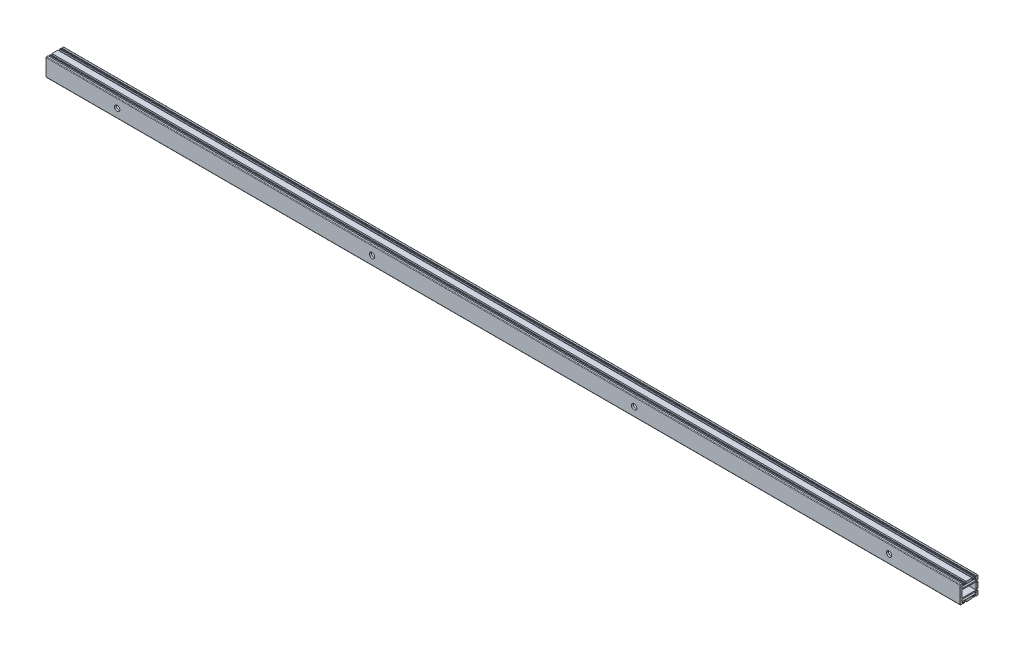
SolidWorks part; units mm, degrees
ref_plane "前视基准面" through (0, 0, 0) normal (0, 0, 1) x (1, 0, 0)
ref_plane "上视基准面" through (0, 0, 0) normal (0, 1, 0) x (1, 0, 0)
ref_plane "右视基准面" through (0, 0, 0) normal (1, 0, 0) x (0, 0, -1)
sketch "草图1" plane through (0, 0, 0) normal (1, 0, 0) x (0, 0, -1)
  line L0 (-15, 15) -> (15, -15) construction
  line L1 (-14, 15) -> (-11.5, 15)
  line L2 (-15, 14) -> (-15, -14)
  line L3 (-14, -15) -> (-11.5, -15)
  line L4 (15, 14) -> (15, 8)
  line L5 (15, 15) -> (-15, -15) construction
  line L6 (-11.5, 15) -> (-11.5, 13.5)
  line L7 (-11.5, 13.5) -> (-11.4, 13.5)
  line L8 (-11, 13.1) -> (-11, 12)
  line L9 (-11, 12) -> (-9.5, 12)
  line L10 (-9.5, 12) -> (-9.5, 15)
  line L11 (-9.5, 15) -> (-8, 15)
  line L12 (-8, 15) -> (-8, 12.5)
  line L13 (-8, 12.5) -> (-5, 12.5)
  line L14 (-5, 12.5) -> (-5, 15)
  line L15 (-5, 15) -> (5, 15)
  line L16 (0, 21.5201) -> (0, -18.309) construction
  line L17 (0, 55) -> (0, -55) construction
  line L18 (5, 12.5) -> (5, 15)
  line L19 (8, 12.5) -> (5, 12.5)
  line L20 (8, 15) -> (8, 12.5)
  line L21 (9.5, 15) -> (8, 15)
  line L22 (9.5, 12) -> (9.5, 15)
  line L23 (11, 12) -> (9.5, 12)
  line L24 (11, 13.1) -> (11, 12)
  line L25 (11.5, 13.5) -> (11.4, 13.5)
  line L26 (11.5, 15) -> (11.5, 13.5)
  line L27 (8, 15) -> (9.5, 15)
  line L28 (11.5, 15) -> (14, 15)
  line L29 (-19.8303, 0) -> (22.13, 0) construction
  line L30 (55, 0) -> (-55, 0) construction
  line L31 (8, -15) -> (9.5, -15)
  line L32 (11.5, -15) -> (11.5, -13.5)
  line L33 (11.5, -13.5) -> (11.4, -13.5)
  line L34 (11, -13.1) -> (11, -12)
  line L35 (11, -12) -> (9.5, -12)
  line L36 (9.5, -12) -> (9.5, -15)
  line L37 (9.5, -15) -> (8, -15)
  line L38 (8, -15) -> (8, -12.5)
  line L39 (8, -12.5) -> (5, -12.5)
  line L40 (5, -12.5) -> (5, -15)
  line L41 (-5, -15) -> (5, -15)
  line L42 (-5, -12.5) -> (-5, -15)
  line L43 (-8, -12.5) -> (-5, -12.5)
  line L44 (-8, -15) -> (-8, -12.5)
  line L45 (-9.5, -15) -> (-8, -15)
  line L46 (-9.5, -12) -> (-9.5, -15)
  line L47 (-11, -12) -> (-9.5, -12)
  line L48 (-11, -13.1) -> (-11, -12)
  line L49 (-11.5, -13.5) -> (-11.4, -13.5)
  line L50 (-11.5, -15) -> (-11.5, -13.5)
  line L51 (-9.5, -15) -> (-8, -15)
  line L52 (-5, -15) -> (5, -15)
  line L53 (8, -15) -> (9.5, -15)
  line L54 (11.5, -15) -> (14, -15)
  line L55 (15, 8) -> (12.5, 8)
  line L56 (12.5, 8) -> (12.5, 5)
  line L57 (12.5, 5) -> (15, 5)
  line L58 (12.5, -5) -> (15, -5)
  line L59 (12.5, -8) -> (12.5, -5)
  line L60 (15, -8) -> (12.5, -8)
  line L61 (15, 5) -> (15, -5)
  line L62 (15, -8) -> (15, -14)
  line L63 (12, -10.5) -> (12, -8.5)
  line L64 (-11.5, 11) -> (11.5, 11)
  line L65 (-12, 10.5) -> (-12, 8.5)
  line L66 (-11.5, 8) -> (11.5, 8)
  line L67 (12, 10.5) -> (12, 8.5)
  line L68 (-11.5, -8) -> (11.5, -8)
  line L69 (-12, -10.5) -> (-12, -8.5)
  line L70 (-11.5, -11) -> (11.5, -11)
  line L72 (-11.75, 6) -> (11.75, 6)
  line L73 (-11.75, 6) -> (-11.75, -6)
  line L74 (-11.75, -6) -> (11.75, -6)
  line L75 (11.75, 6) -> (11.75, -6)
  arc A0 (12, 8.5) -> (11.5, 8) centre (11.5, 8.5) cw
  arc A1 (11.5, 11) -> (12, 10.5) centre (11.5, 10.5) cw
  arc A2 (-11.5, 11) -> (-12, 10.5) centre (-11.5, 10.5) ccw
  arc A3 (-11.5, 8) -> (-12, 8.5) centre (-11.5, 8.5) cw
  arc A4 (-11, -13.1) -> (-11.4, -13.5) centre (-11.4, -13.1) cw
  arc A5 (11.4, -13.5) -> (11, -13.1) centre (11.4, -13.1) cw
  arc A6 (11.4, 13.5) -> (11, 13.1) centre (11.4, 13.1) ccw
  arc A7 (-11, 13.1) -> (-11.4, 13.5) centre (-11.4, 13.1) ccw
  arc A8 (-11.5, -8) -> (-12, -8.5) centre (-11.5, -8.5) ccw
  arc A9 (-11.5, -11) -> (-12, -10.5) centre (-11.5, -10.5) cw
  arc A10 (11.5, -11) -> (12, -10.5) centre (11.5, -10.5) ccw
  arc A11 (12, -8.5) -> (11.5, -8) centre (11.5, -8.5) ccw
  arc A12 (14, 15) -> (15, 14) centre (14, 14) cw
  arc A13 (14, -15) -> (15, -14) centre (14, -14) ccw
  arc A14 (-15, -14) -> (-14, -15) centre (-14, -14) ccw
  arc A15 (-15, 14) -> (-14, 15) centre (-14, 14) cw
  point P69 (12, 11)
  point P72 (-12, 11)
  point P77 (-11, -13.5)
  point P80 (11, -13.5)
  point P83 (11, 13.5)
  point P86 (-11, 13.5)
  point P99 (-12, -11)
  point P100 (12, -11)
  dimension "D17" = 0.5
  dimension "D18" = 0.4
  dimension "D21" = 1
  dimension "D1" = 3.5
  dimension "D2" = 1.5
  dimension "D3" = 0.5
  dimension "D4" = 1.5
  dimension "D5" = 3
  dimension "D6" = 30
  dimension "D7" = 30
  dimension "D8" = 1.5
  dimension "D9" = 2.5
  dimension "D10" = 3
  dimension "D11" = 2.5
  dimension "D12" = 7
  dimension "D13" = 3
  dimension "D14" = 4
  dimension "D15" = 3
  dimension "D16" = 24
  dimension "D19" = 23.5
  dimension "D20" = 12
extrude "凸台-拉伸1" add sketch "草图1" along normal mid plane 1542 contours A15 L2 A14 L3 L50 L49 A4 L48 L47 L46 L45 L44 L43 L42 L41 L40 L39 L38 L31 L36 L35 L34 A5 L33 L32 L54 A13 L62 L60 L59 L58 L61 L57 L56 L55 L4 A12 L28 L26 L25 A6 L24 L23 L22 L21 L20 L19 L18 L15 L14 L13
hole_wizard "M6 螺纹孔1" positions "草图3" profile "草图2" tap size "M6" standard "GB"
sketch "草图3" plane through (0, 0, -15) normal (0, 0, -1) x (-1, 0, 0)
  line L0 (771, 5) -> (771, -5) construction
  line L1 (-771, 15) -> (771, 15) construction
  point P0 (751, 0)
  point P1 (736, 0)
  point P4 (566, 0)
  point P7 (551, 0)
  point P10 (481, 0)
  point P13 (466, 0)
  point P16 (-466, 0)
  point P19 (-481, 0)
  point P22 (-551, 0)
  point P25 (-566, 0)
  point P28 (-736, 0)
  point P31 (-751, 0)
  dimension "D1" = 20
  dimension "D2" = 15
sketch "草图2" plane through (-751, 0, -15) normal (1, 0, 0) x (0, 1, 0)
  line L0 (0, 0) -> (0, 16.5022)
  line L1 (0, 16.5022) -> (2.5, 15)
  line L2 (2.5, 15) -> (2.5, 0)
  line L5 (2.5, 0) -> (0, 0)
  line L10 (0, 16.5022) -> (-2.5, 15) construction
  line L11 (0, -6.35) -> (0, 107.95) construction
  dimension "螺纹孔钻头直径" = 5
  dimension "螺纹孔钻头深度" = 15
  dimension "导头角度" = 118
cosmetic thread "孔螺蚊线1" parameters "D1"=3.25, "D2"=6
cosmetic thread "孔螺蚊线2" parameters "D1"=3.25, "D2"=6
cosmetic thread "孔螺蚊线3" parameters "D1"=3.25, "D2"=6
cosmetic thread "孔螺蚊线4" parameters "D1"=3.25, "D2"=6
cosmetic thread "孔螺蚊线5" parameters "D1"=3.25, "D2"=6
cosmetic thread "孔螺蚊线6" parameters "D1"=3.25, "D2"=6
cosmetic thread "孔螺蚊线7" parameters "D1"=3.25, "D2"=6
cosmetic thread "孔螺蚊线8" parameters "D1"=3.25, "D2"=6
cosmetic thread "孔螺蚊线9" parameters "D1"=3.25, "D2"=6
cosmetic thread "孔螺蚊线10" parameters "D1"=3.25, "D2"=6
cosmetic thread "孔螺蚊线11" parameters "D1"=3.25, "D2"=6
cosmetic thread "孔螺蚊线12" parameters "D1"=3.25, "D2"=6
hole_wizard "M6 螺纹孔2" positions "草图5" profile "草图4" tap size "M6" standard "GB"
sketch "草图5" plane through (0, -15, 0) normal (0, -1, 0) x (1, 0, 0)
  line L0 (771, 5) -> (771, -5) construction
  line L1 (771, -15) -> (-771, -15) construction
  point P0 (751, 0)
  point P1 (736, 0)
  point P4 (-736, 0)
  point P7 (-751, 0)
  dimension "D1" = 20
  dimension "D2" = 15
sketch "草图4" plane through (751, -15, 0) normal (1, 0, 0) x (0, 0, -1)
  line L0 (0, 0) -> (0, 16.5022)
  line L1 (0, 16.5022) -> (2.5, 15)
  line L2 (2.5, 15) -> (2.5, 0)
  line L5 (2.5, 0) -> (0, 0)
  line L10 (0, 16.5022) -> (-2.5, 15) construction
  line L11 (0, -6.35) -> (0, 107.95) construction
  dimension "螺纹孔钻头直径" = 5
  dimension "螺纹孔钻头深度" = 15
  dimension "导头角度" = 118
cosmetic thread "孔螺蚊线13" parameters "D1"=9, "D2"=6
cosmetic thread "孔螺蚊线14" parameters "D1"=9, "D2"=6
cosmetic thread "孔螺蚊线15" parameters "D1"=9, "D2"=6
cosmetic thread "孔螺蚊线16" parameters "D1"=9, "D2"=6
sketch "草图7" plane through (0, 0, 15) normal (0, 0, 1) x (1, 0, 0)
  line L0 (-771, 0) -> (771, 0) construction
  line L1 (-771, 14) -> (-771, -14) construction
  line L2 (771, 14) -> (771, -14) construction
  circle A0 centre (-651, 0) radius 4.5
  circle A1 centre (-221, 0) radius 4.5
  circle A2 centre (651, 0) radius 4.5
  circle A3 centre (221, 0) radius 4.5
  dimension "D5" = 9
  dimension "D1" = 120
  dimension "D2" = 430
  dimension "D3" = 120
  dimension "D4" = 430
extrude "切除-拉伸1" cut sketch "草图7" against normal through all
hole_wizard "M4 螺纹孔1" positions "草图9" profile "草图8" tap size "M4" standard "GB"
sketch "草图9" plane through (0, -15, 0) normal (0, -1, 0) x (1, 0, 0)
  line L0 (771, -15) -> (-771, -15) construction
  line L1 (-771, -11.5) -> (-771, -14) construction
  line L2 (771, 5) -> (771, -5) construction
  point P0 (-151, 0)
  point P1 (-133, 0)
  point P3 (133, 0)
  point P5 (151, 0)
  dimension "D1" = 15
  dimension "D2" = 620
  dimension "D3" = 18
  dimension "D4" = 18
  dimension "D5" = 620
sketch "草图8" plane through (-151, -15, 0) normal (1, 0, 0) x (0, 0, -1)
  line L0 (0, 0) -> (0, 11.0914)
  line L1 (0, 11.0914) -> (1.65, 10.1)
  line L2 (1.65, 10.1) -> (1.65, 0)
  line L5 (1.65, 0) -> (0, 0)
  line L10 (0, 11.0914) -> (-1.65, 10.1) construction
  line L11 (0, -6.35) -> (0, 107.95) construction
  dimension "螺纹孔钻头直径" = 3.3
  dimension "螺纹孔钻头深度" = 10.1
  dimension "导头角度" = 118
cosmetic thread "孔螺蚊线17" parameters "D1"=8, "D2"=4
cosmetic thread "孔螺蚊线18" parameters "D1"=8, "D2"=4
cosmetic thread "孔螺蚊线19" parameters "D1"=8, "D2"=4
cosmetic thread "孔螺蚊线20" parameters "D1"=8, "D2"=4
